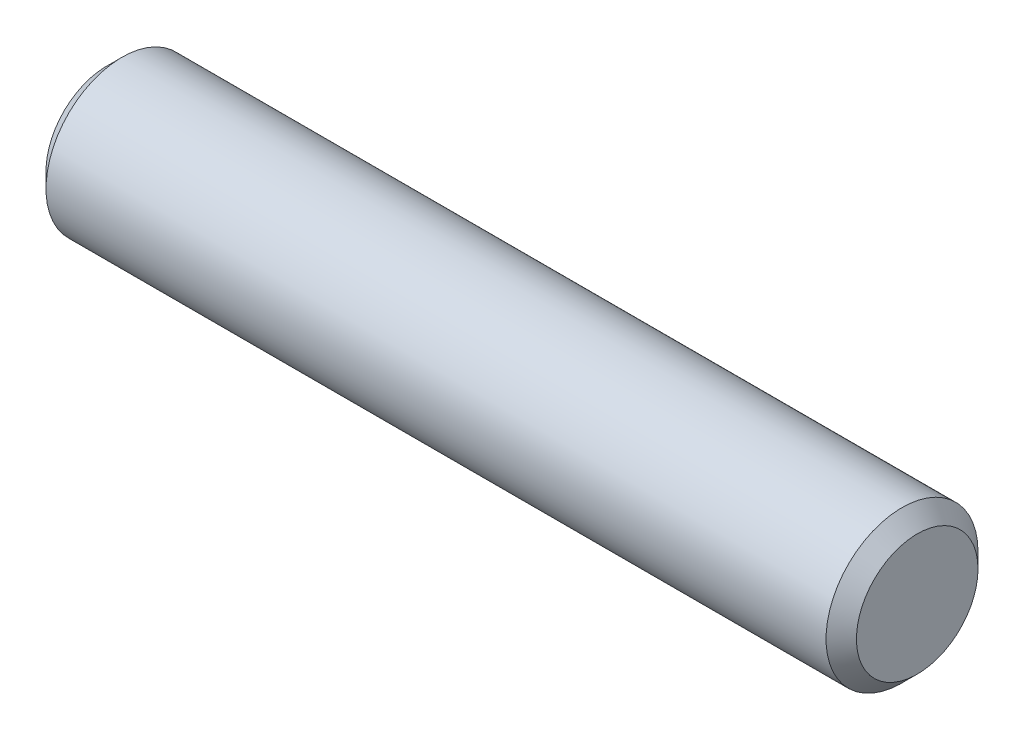
SolidWorks part; units mm, degrees
material "Plain Carbon Steel"
ref_plane "Front" through (0, 0, 0) normal (0, 0, 1) x (1, 0, 0)
ref_plane "Top" through (0, 0, 0) normal (0, 1, 0) x (1, 0, 0)
ref_plane "Right" through (0, 0, 0) normal (1, 0, 0) x (0, 0, -1)
sketch "Sketch1" plane through (0, 0, 0) normal (0, 0, 1) x (1, 0, 0)
  line L0 (-25.4, 0) -> (25.4, 0) construction
  line L1 (25.4, 4.7625) -> (25.4, -4.7625) construction
  line L2 (-25.4, 4.7625) -> (-25.4, -4.7625) construction
  dimension "Length" = 50.8
  dimension "Diameter" = 9.525
sketch "Sketch2" plane through (0, 0, 0) normal (1, 0, 0) x (0, 0, -1)
  circle A0 centre (0, 0) radius 4.7625
extrude "Extrude1" add sketch "Sketch2" against normal up to vertex (25.4 mm away) and the other way up to vertex (25.4 mm away) up to point (-25.4, 4.7625, 0) other way up to point (25.4, 4.7625, 0)
chamfer "Chamfer1" distance 0.9525 angle 45 2 edges at (25.4, 0, -4.7625) (-25.4, 0, -4.7625)
equation "\"D1@Chamfer1\" = \"Diameter@Sketch1\"*.1"
